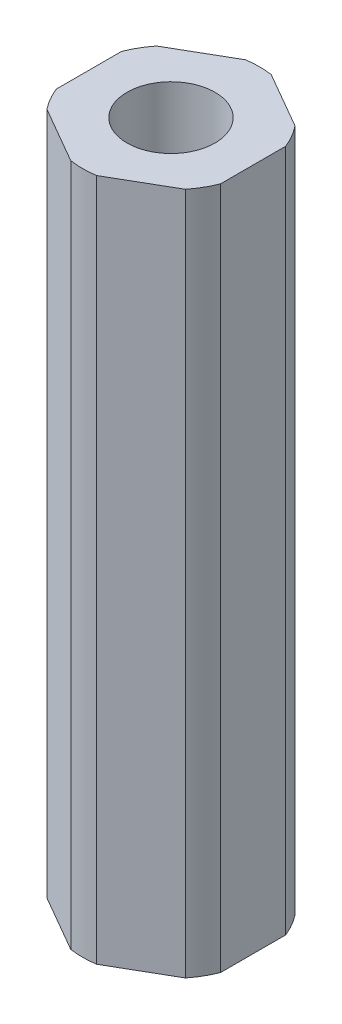
SolidWorks part; units mm, degrees
ref_plane "Front Plane" through (0, 0, 0) normal (0, 0, 1) x (1, 0, 0)
ref_plane "Top Plane" through (0, 0, 0) normal (0, 1, 0) x (1, 0, 0)
ref_plane "Right Plane" through (0, 0, 0) normal (1, 0, 0) x (0, 0, -1)
sketch "Sketch1" plane through (0, 0, 0) normal (0, 1, 0) x (1, 0, 0)
  line L1 (-0.743, 5.0703) -> (-4.0195, 3.1786)
  line L2 (-4.7625, 1.8917) -> (-4.7625, -1.8917)
  line L3 (-4.0195, -3.1786) -> (-0.743, -5.0703)
  line L4 (0.743, -5.0703) -> (4.0195, -3.1786)
  line L5 (4.7625, -1.8917) -> (4.7625, 1.8917)
  line L6 (4.0195, 3.1786) -> (0.743, 5.0703)
  circle A0 centre (0, 0) radius 4.7625 construction
  arc A1 (-4.7625, -1.8917) -> (-4.0195, -3.1786) centre (0, 0) ccw
  arc A2 (-4.0195, 3.1786) -> (-4.7625, 1.8917) centre (0, 0) ccw
  arc A3 (0.743, 5.0703) -> (-0.743, 5.0703) centre (0, 0) ccw
  arc A4 (4.7625, 1.8917) -> (4.0195, 3.1786) centre (0, 0) ccw
  arc A5 (4.0195, -3.1786) -> (4.7625, -1.8917) centre (0, 0) ccw
  arc A6 (-0.743, -5.0703) -> (0.743, -5.0703) centre (0, 0) ccw
  dimension "D1" = 9.525
  dimension "D2" = 10.2489
extrude "Boss-Extrude1" add sketch "Sketch1" along normal blind 39.624 contours A2 L2 A1 L3 A6 L4 A5 L5 A4 L6 A3 L1
sketch "Sketch2" plane through (0, 39.624, 0) normal (0, 1, 0) x (1, 0, 0)
  circle A0 centre (0, 0) radius 2.5527
  dimension "D1" = 5.1054
extrude "Cut-Extrude1" cut sketch "Sketch2" against normal through all
